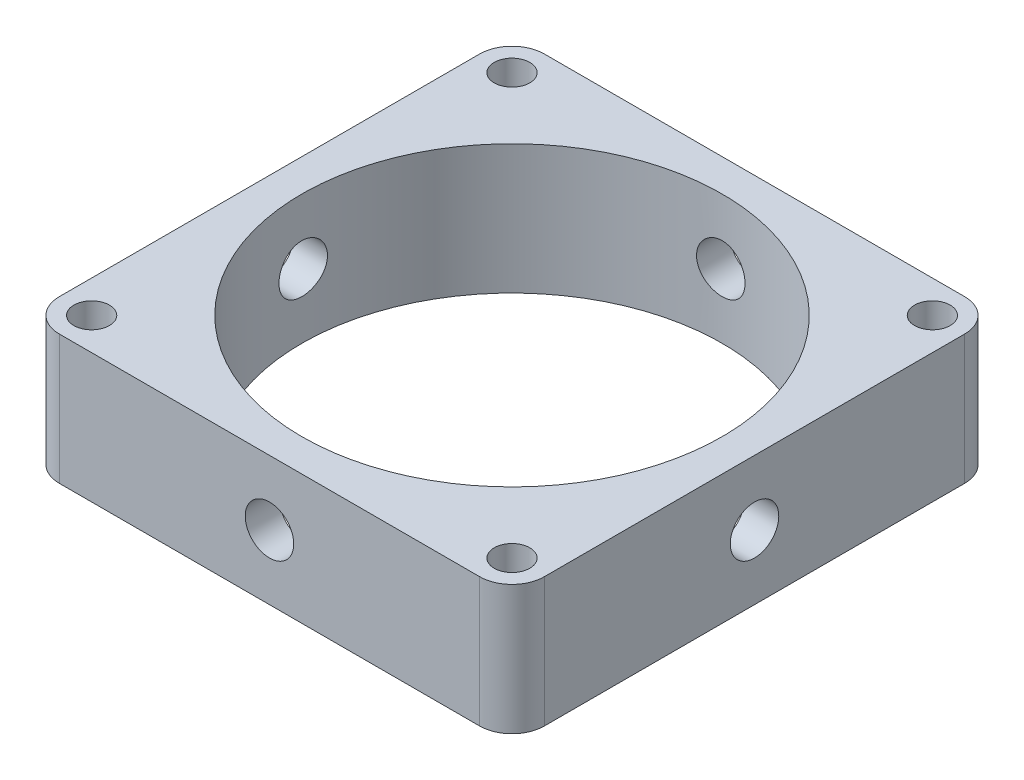
SolidWorks part; units mm, degrees
ref_plane "Front Plane" through (0, 0, 0) normal (0, 0, 1) x (1, 0, 0)
ref_plane "Top Plane" through (0, 0, 0) normal (0, 1, 0) x (1, 0, 0)
ref_plane "Right Plane" through (0, 0, 0) normal (1, 0, 0) x (0, 0, -1)
sketch "Sketch1" plane through (0, 0, 0) normal (0, 1, 0) x (1, 0, 0)
  line L1 (-38.1, -38.1) -> (38.1, -38.1)
  line L2 (-38.1, -38.1) -> (-38.1, 38.1)
  line L3 (-38.1, 38.1) -> (38.1, 38.1)
  line L4 (38.1, -38.1) -> (38.1, 38.1)
  line L5 (-38.1, -38.1) -> (38.1, 38.1) construction
  line L6 (-38.1, 38.1) -> (38.1, -38.1) construction
  circle A0 centre (33.02, 33.02) radius 2.794
  circle A1 centre (33.02, -33.02) radius 2.794
  circle A2 centre (-33.02, -33.02) radius 2.794
  circle A3 centre (-33.02, 33.02) radius 2.794
  circle A4 centre (0, 0) radius 38.1 construction
  circle A5 centre (0, 0) radius 33.02
  point P0 (0, 0)
  point P17 (0, 0)
  dimension "D3" = 5.588
  dimension "D4" = 5.08
  dimension "D1" = 76.2
  dimension "D2" = 76.2
  dimension "D6" = 5.08
  dimension "D5" = 4
extrude "Boss-Extrude1" add sketch "Sketch1" along normal blind 20.32
fillet "Fillet1" radius 5.08 4 edges at (-38.1, 10.16, -38.1) (-38.1, 10.16, 38.1) (38.1, 10.16, -38.1) (38.1, 10.16, 38.1)
sketch "Sketch2" plane through (0, 0, 38.1) normal (0, 0, 1) x (1, 0, 0)
  line L0 (0, 20.32) -> (0, 0)
  line L1 (-33.02, 20.32) -> (33.02, 20.32) construction
  circle A0 centre (0, 10.16) radius 3.81
  dimension "D1" = 7.62
extrude "Cut-Extrude1" cut sketch "Sketch2" against normal through all contours L0 A0
sketch "Sketch3" plane through (38.1, 0, 0) normal (1, 0, 0) x (0, 0, -1)
  line L0 (0, 0) -> (0, 20.32)
  line L1 (-33.02, 20.32) -> (33.02, 20.32) construction
  circle A0 centre (0, 10.16) radius 3.81
  dimension "D1" = 7.62
extrude "Cut-Extrude2" cut sketch "Sketch3" against normal through all contours L0 A0 | L0 A0
